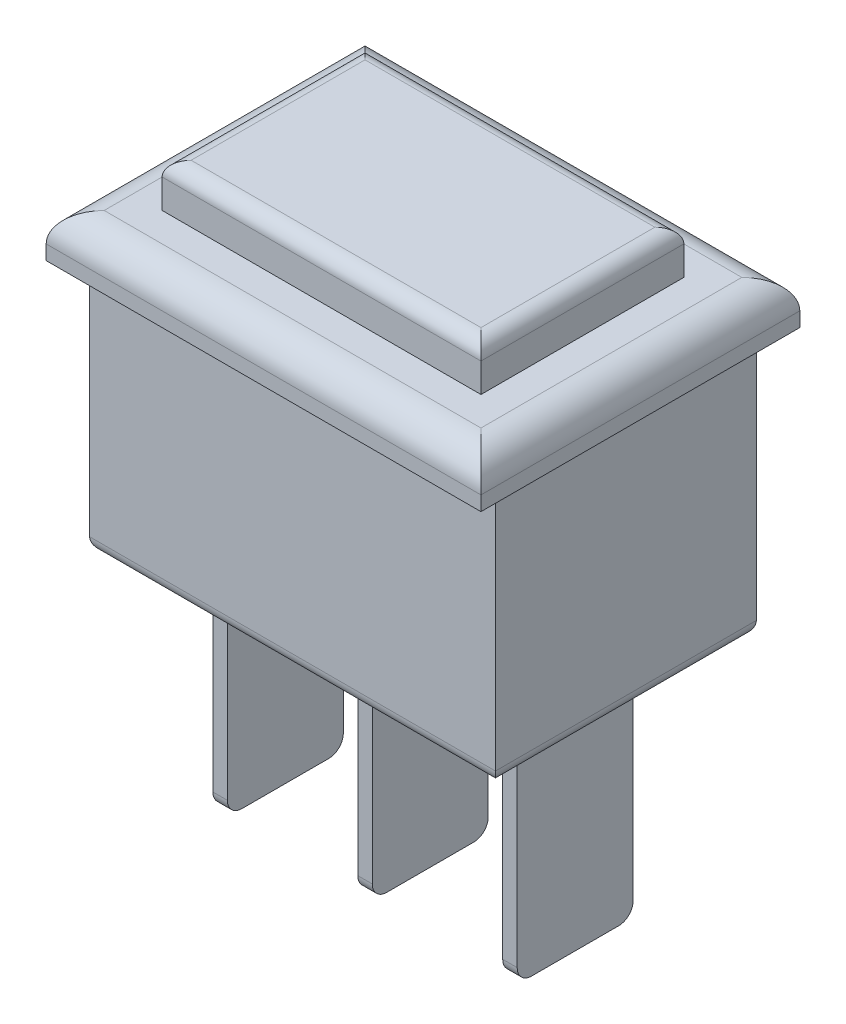
SolidWorks part; units mm, degrees
ref_plane "Спереди" through (0, 0, 0) normal (0, 0, 1) x (1, 0, 0)
ref_plane "Сверху" through (0, 0, 0) normal (0, 1, 0) x (1, 0, 0)
ref_plane "Справа" through (0, 0, 0) normal (1, 0, 0) x (0, 0, -1)
sketch "Эскиз1" plane through (0, 0, 0) normal (0, 1, 0) x (1, 0, 0)
  line L1 (-7, -4.5) -> (7, -4.5)
  line L2 (-7, -4.5) -> (-7, 4.5)
  line L3 (-7, 4.5) -> (7, 4.5)
  line L4 (7, -4.5) -> (7, 4.5)
  line L5 (-7, -4.5) -> (7, 4.5) construction
  line L6 (-7, 4.5) -> (7, -4.5) construction
  point P0 (0, 0)
  dimension "D1" = 14
  dimension "D2" = 9
extrude "Бобышка-Вытянуть1" add sketch "Эскиз1" along normal blind 9
sketch "Эскиз2" plane through (0, 9, 0) normal (0, 1, 0) x (1, 0, 0)
  line L1 (-7.5, -5.5) -> (7.5, -5.5)
  line L2 (-7.5, -5.5) -> (-7.5, 5.5)
  line L3 (-7.5, 5.5) -> (7.5, 5.5)
  line L4 (7.5, -5.5) -> (7.5, 5.5)
  line L5 (-7.5, -5.5) -> (7.5, 5.5) construction
  line L6 (-7.5, 5.5) -> (7.5, -5.5) construction
  point P0 (0, 0)
  dimension "D1" = 15
  dimension "D2" = 11
extrude "Бобышка-Вытянуть2" add sketch "Эскиз2" along normal blind 1.5
sketch "Эскиз3" plane through (0, 10.5, 0) normal (0, 1, 0) x (1, 0, 0)
  line L1 (-5.5, -3.5) -> (5.5, -3.5)
  line L2 (-5.5, -3.5) -> (-5.5, 3.5)
  line L3 (-5.5, 3.5) -> (5.5, 3.5)
  line L4 (5.5, -3.5) -> (5.5, 3.5)
  line L5 (-5.5, -3.5) -> (5.5, 3.5) construction
  line L6 (-5.5, 3.5) -> (5.5, -3.5) construction
  point P0 (0, 0)
  dimension "D1" = 11
  dimension "D2" = 7
extrude "Бобышка-Вытянуть3" add sketch "Эскиз3" along normal blind 1.5
sketch "Эскиз4" plane through (0, 0, 0) normal (0, -1, 0) x (1, 0, 0)
  line L0 (-1000, 0) -> (49000, 0) construction
  line L1 (4.75, 2) -> (5.25, 2)
  line L2 (-0.25, -2) -> (0.25, -2)
  line L3 (-0.25, -2) -> (-0.25, 2)
  line L4 (-0.25, 2) -> (0.25, 2)
  line L5 (0.25, -2) -> (0.25, 2)
  line L6 (-0.25, -2) -> (0.25, 2) construction
  line L7 (-0.25, 2) -> (0.25, -2) construction
  line L8 (5.25, -2) -> (5.25, 2)
  line L9 (4.75, -2) -> (5.25, 2) construction
  line L10 (4.75, -2) -> (4.75, 2)
  line L11 (4.75, 2) -> (5.25, -2) construction
  line L12 (4.75, -2) -> (5.25, -2)
  line L13 (-0.25, 2) -> (0.25, 2)
  line L14 (0.25, -2) -> (0.25, 2)
  line L15 (-0.25, -2) -> (0.25, 2) construction
  line L16 (-0.25, -2) -> (-0.25, 2)
  line L17 (-0.25, 2) -> (0.25, -2) construction
  line L18 (-0.25, -2) -> (0.25, -2)
  line L19 (-5.25, 2) -> (-4.75, 2)
  line L20 (-4.75, -2) -> (-4.75, 2)
  line L21 (-5.25, -2) -> (-4.75, 2) construction
  line L22 (-5.25, -2) -> (-5.25, 2)
  line L23 (-5.25, 2) -> (-4.75, -2) construction
  line L24 (-5.25, -2) -> (-4.75, -2)
  line L25 (-0.25, 2) -> (4.75, 2) construction
  point P1 (0, 0)
  point P8 (0, 0)
  point P9 (-5, 0)
  dimension "D1" = 0.5
  dimension "D2" = 4
  dimension "D5" = 5
  dimension "D6" = 5
  dimension "D3" = 2
  dimension "D4" = 2
extrude "Бобышка-Вытянуть4" add sketch "Эскиз4" along normal blind 8 contours L2 L5 L4 L3 | L10 L12 L8 L1 | L22 L24 L20 L19
fillet "Скругление1" radius 1 4 edges at (7.5, 10.5, 0) (0, 10.5, 5.5) (0, 10.5, -5.5) (-7.5, 10.5, 0)
fillet "Скругление2" radius 0.5 4 edges at (5.5, 12, 0) (0, 12, -3.5) (-5.5, 12, 0) (0, 12, 3.5)
fillet "Скругление3" radius 0.5 4 edges at (7, 0, 0) (0, 0, -4.5) (-7, 0, 0) (0, 0, 4.5)
fillet "Скругление4" radius 0.5 18 edges at (5, 0, -2) (4.75, 0, 0) (5, 0, 2) (5.25, 0, 0) (0, 0, 2) (-5, 0, -2) (-5, 0, 2) (0, 0, -2) (0.25, 0, 0) (-0.25, 0, 0) (-5.25, 0, 0) (-4.75, 0, 0) (-5, -8, 2) (-5, -8, -2) (0, -8, 2) (0, -8, -2) (5, -8, 2) (5, -8, -2)
